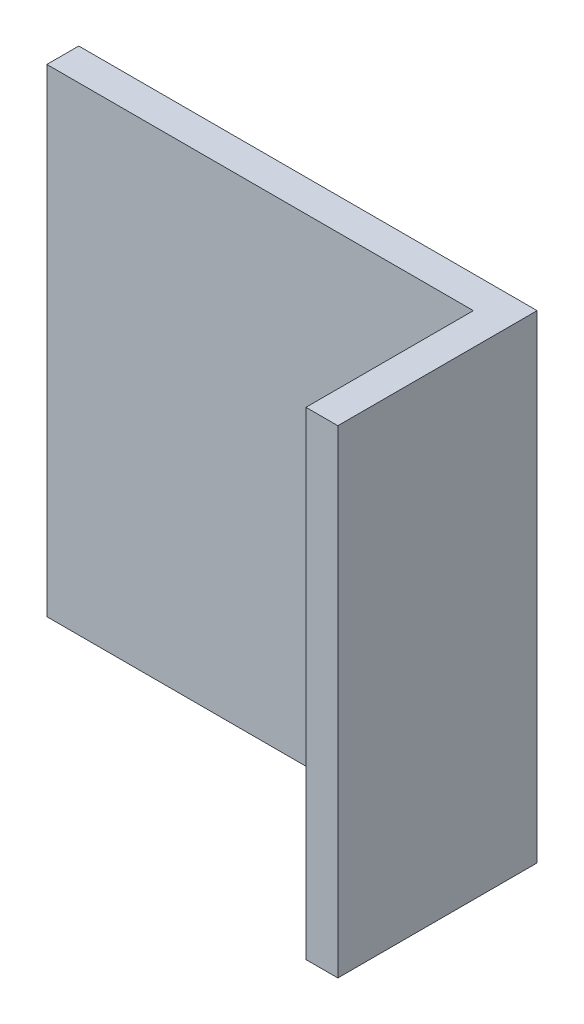
SolidWorks part; units mm, degrees
ref_plane "前视基准面" through (0, 0, 0) normal (0, 0, 1) x (1, 0, 0)
ref_plane "上视基准面" through (0, 0, 0) normal (0, 1, 0) x (1, 0, 0)
ref_plane "右视基准面" through (0, 0, 0) normal (1, 0, 0) x (0, 0, -1)
sketch "草图1" plane through (0, 0, 0) normal (0, 0, 1) x (1, 0, 0)
  line L1 (115, -120) -> (-115, -120)
  line L2 (115, -120) -> (115, 120)
  line L3 (115, 120) -> (-115, 120)
  line L4 (-115, -120) -> (-115, 120)
  line L5 (115, -120) -> (-115, 120) construction
  line L6 (115, 120) -> (-115, -120) construction
  point P0 (0, 0)
  dimension "D1" = 230
  dimension "D2" = 240
extrude "凸台-拉伸1" add sketch "草图1" along normal blind 16
sketch "草图4" plane through (0, 0, 16) normal (0, 0, 1) x (1, 0, 0)
  line L0 (115, 120) -> (-115, 120) construction
  line L1 (115, -120) -> (99, -120)
  line L2 (115, -120) -> (115, 120)
  line L3 (115, 120) -> (99, 120)
  line L4 (99, -120) -> (99, 120)
  dimension "D1" = 16
extrude "凸台-拉伸2" add sketch "草图4" along normal blind 84
